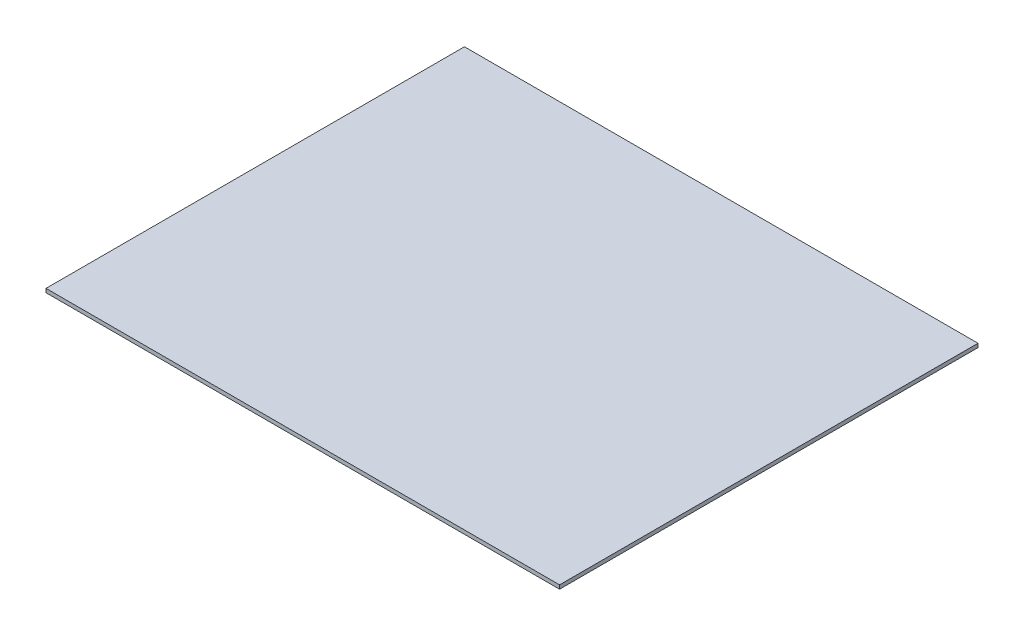
SolidWorks part; units mm, degrees
ref_plane "Front Plane" through (0, 0, 0) normal (0, 0, 1) x (1, 0, 0)
ref_plane "Top Plane" through (0, 0, 0) normal (0, 1, 0) x (1, 0, 0)
ref_plane "Right Plane" through (0, 0, 0) normal (1, 0, 0) x (0, 0, -1)
sketch "Sketch1" plane through (0, 0, 0) normal (0, 1, 0) x (1, 0, 0)
  line L1 (1350, -1100) -> (-1350, -1100)
  line L2 (1350, -1100) -> (1350, 1100)
  line L3 (1350, 1100) -> (-1350, 1100)
  line L4 (-1350, -1100) -> (-1350, 1100)
  line L5 (1350, -1100) -> (-1350, 1100) construction
  line L6 (1350, 1100) -> (-1350, -1100) construction
  point P0 (0, 0)
extrude "Boss-Extrude1" add sketch "Sketch1" along normal blind 20
